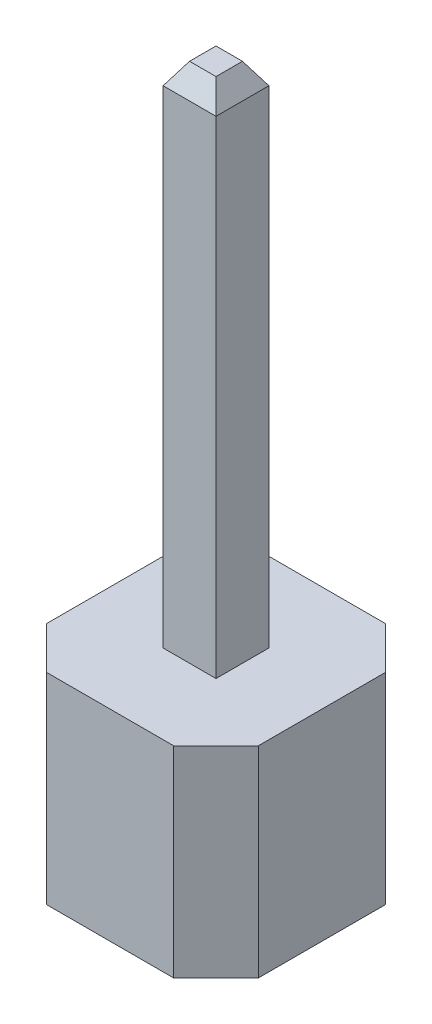
SolidWorks part; units mm, degrees
ref_plane "Front" through (0, 0, 0) normal (0, 0, 1) x (1, 0, 0)
ref_plane "Top" through (0, 0, 0) normal (0, 1, 0) x (1, 0, 0)
ref_plane "Right" through (0, 0, 0) normal (1, 0, 0) x (0, 0, -1)
sketch "Sketch1" plane through (0, 0, 0) normal (0, 1, 0) x (1, 0, 0)
  line L1 (-1.27, 1.27) -> (1.27, 1.27)
  line L2 (-1.27, 1.27) -> (-1.27, -1.27)
  line L3 (-1.27, -1.27) -> (1.27, -1.27)
  line L4 (1.27, 1.27) -> (1.27, -1.27)
  line L5 (-1.27, 1.27) -> (1.27, -1.27) construction
  line L6 (-1.27, -1.27) -> (1.27, 1.27) construction
  point P0 (0, 0)
  dimension "D1" = 2.54
  dimension "D2" = 2.54
extrude "Boss-Extrude1" add sketch "Sketch1" along normal blind 2.413
chamfer "Chamfer1" distance 0.508 angle 45 4 edges at (-1.27, 1.2065, 1.27) (-1.27, 1.2065, -1.27) (1.27, 1.2065, -1.27) (1.27, 1.2065, 1.27)
sketch "Sketch2" plane through (0, 2.413, 0) normal (0, 1, 0) x (1, 0, 0)
  line L1 (-0.3175, -0.3175) -> (0.3175, -0.3175)
  line L2 (-0.3175, -0.3175) -> (-0.3175, 0.3175)
  line L3 (-0.3175, 0.3175) -> (0.3175, 0.3175)
  line L4 (0.3175, -0.3175) -> (0.3175, 0.3175)
  line L5 (-0.3175, -0.3175) -> (0.3175, 0.3175) construction
  line L6 (-0.3175, 0.3175) -> (0.3175, -0.3175) construction
  point P0 (0, 0)
  dimension "D1" = 0.635
  dimension "D2" = 0.635
extrude "Boss-Extrude2" add sketch "Sketch2" along normal blind 6.096
chamfer "Chamfer2" distance 0.254 angle 32 4 edges at (0, 8.509, 0.3175) (-0.3175, 8.509, 0) (0, 8.509, -0.3175) (0.3175, 8.509, 0)
